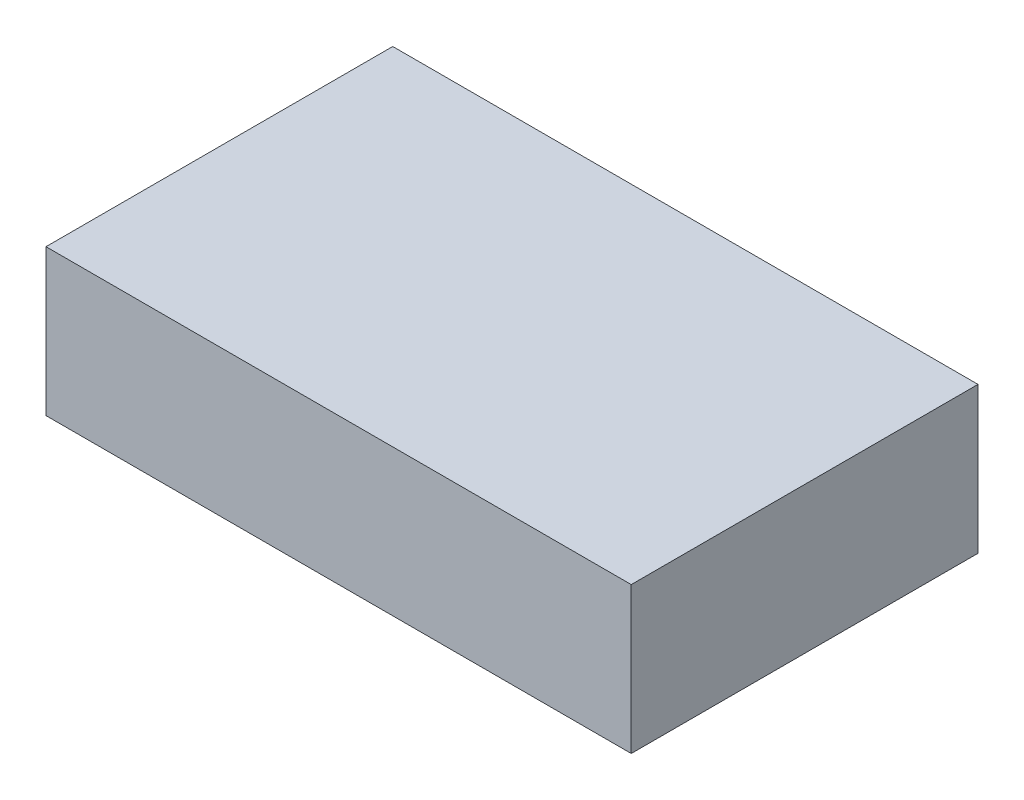
SolidWorks part; units mm, degrees
ref_plane "Front Plane" through (0, 0, 0) normal (0, 0, 1) x (1, 0, 0)
ref_plane "Top Plane" through (0, 0, 0) normal (0, 1, 0) x (1, 0, 0)
ref_plane "Right Plane" through (0, 0, 0) normal (1, 0, 0) x (0, 0, -1)
sketch "Sketch1" plane through (0, 0, 0) normal (0, 1, 0) x (1, 0, 0)
  line L1 (0, 0) -> (40, 0)
  line L2 (0, 0) -> (0, 23.7)
  line L3 (0, 23.7) -> (40, 23.7)
  line L4 (40, 0) -> (40, 23.7)
extrude "Boss-Extrude1" add sketch "Sketch1" along normal blind 10
